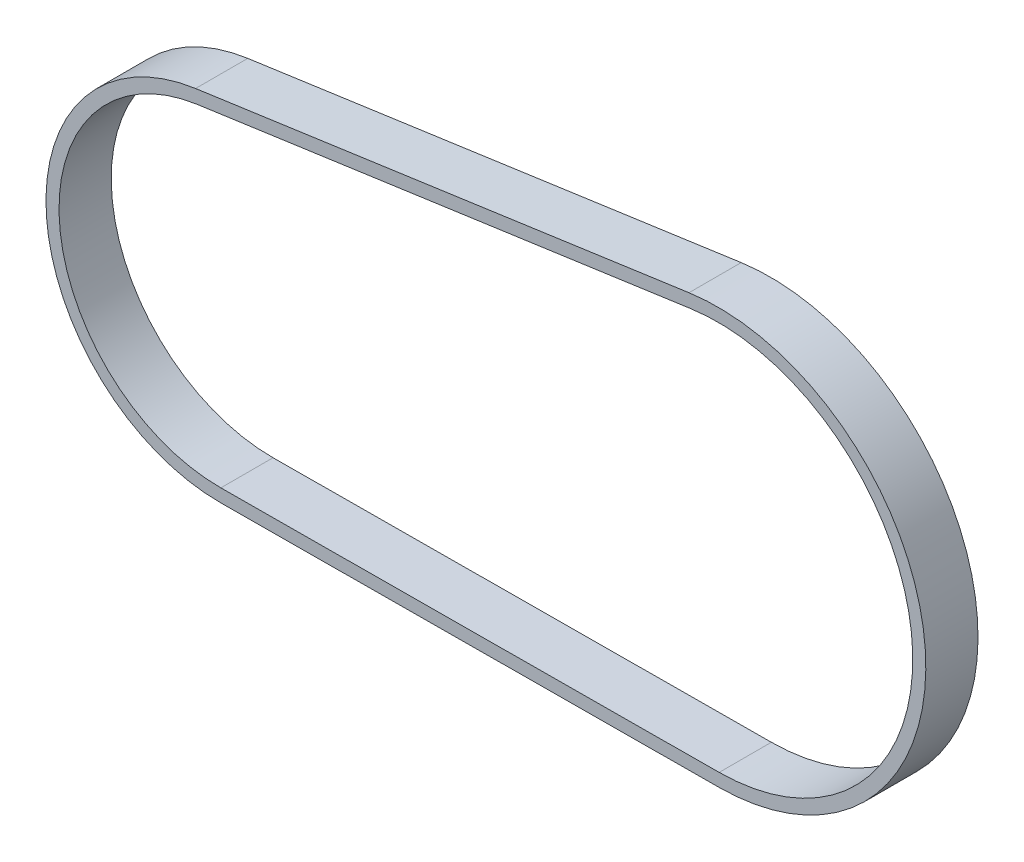
SolidWorks part; units mm, degrees
ref_plane "Front Plane" through (0, 0, 0) normal (0, 0, 1) x (1, 0, 0)
ref_plane "Top Plane" through (0, 0, 0) normal (0, 1, 0) x (1, 0, 0)
ref_plane "Right Plane" through (0, 0, 0) normal (1, 0, 0) x (0, 0, -1)
sketch "Sketch2" plane through (0, 0, 0) normal (0, 0, 1) x (1, 0, 0)
  line L0 (0, 0) -> (1, 0) construction
  line L1 (0, 0) -> (0, 1) construction
  line L6 (-2.8035, 19.8025) -> (53.9132, 27.8322)
  line L7 (57.3918, -19.6837) -> (0.1103, -19.9997)
  arc A2 (53.9132, 27.8322) -> (57.3918, -19.6837) centre (57.2601, 4.1919) cw
  arc A4 (0.1103, -19.9997) -> (-2.8035, 19.8025) centre (0, 0) cw
extrude "Extrude-Thin1" add sketch "Sketch2" against normal blind 6 thin
